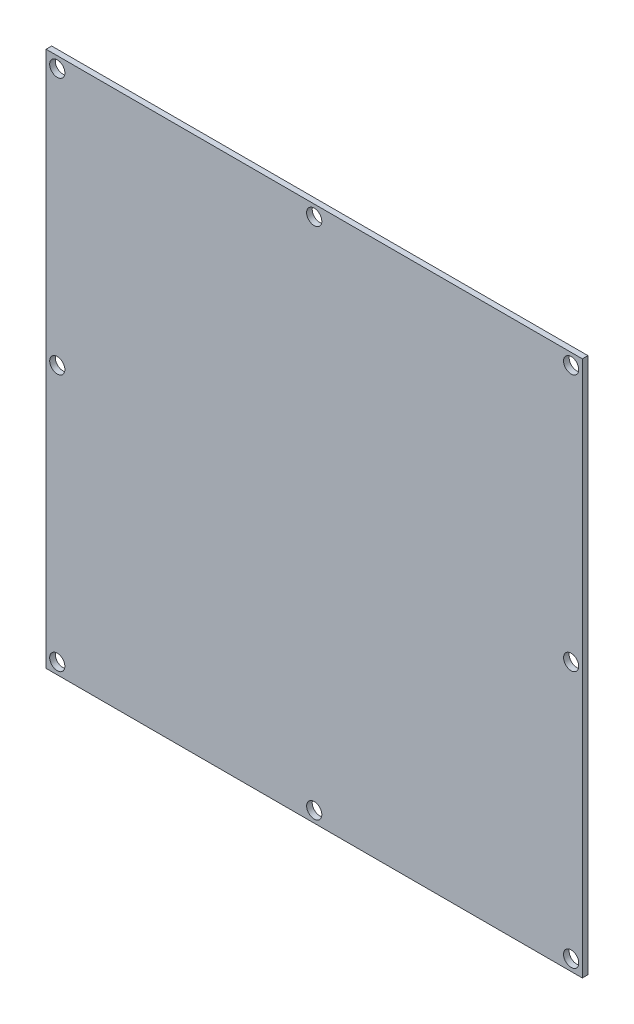
SolidWorks part; units mm, degrees
ref_plane "Front Plane" through (0, 0, 0) normal (0, 0, 1) x (1, 0, 0)
ref_plane "Top Plane" through (0, 0, 0) normal (0, 1, 0) x (1, 0, 0)
ref_plane "Right Plane" through (0, 0, 0) normal (1, 0, 0) x (0, 0, -1)
sketch "Sketch1" plane through (0, 0, 0) normal (0, 0, 1) x (1, 0, 0)
  line L1 (0, 0) -> (152.4, 0)
  line L2 (0, 0) -> (0, 152.4)
  line L3 (0, 152.4) -> (152.4, 152.4)
  line L4 (152.4, 0) -> (152.4, 152.4)
  dimension "D1" = 152.4
  dimension "D2" = 152.4
extrude "Boss-Extrude1" add sketch "Sketch1" along normal blind 1.5875
sketch "Sketch2" plane through (0, 0, 1.5875) normal (0, 0, 1) x (1, 0, 0)
  line L24 (3.175, 3.175) -> (149.225, 3.175)
  line L25 (149.225, 3.175) -> (149.225, 149.225)
  line L26 (3.175, 149.225) -> (3.175, 3.175)
  line L27 (149.225, 149.225) -> (3.175, 149.225)
  line L28 (3.175, 3.175) -> (149.225, 3.175) construction
  line L29 (149.225, 3.175) -> (149.225, 149.225) construction
  line L30 (3.175, 149.225) -> (3.175, 3.175) construction
  line L31 (149.225, 149.225) -> (3.175, 149.225) construction
  circle A0 centre (3.175, 149.225) radius 2.159
  circle A1 centre (76.2, 149.225) radius 2.159
  circle A2 centre (149.225, 149.225) radius 2.159
  circle A3 centre (3.175, 3.175) radius 2.159
  circle A4 centre (149.225, 3.175) radius 2.159
  circle A5 centre (149.225, 76.2) radius 2.159
  circle A6 centre (3.175, 76.2) radius 2.159
  circle A9 centre (76.2, 3.175) radius 2.159
  dimension "D2" = 4.318
  dimension "D1" = 3.175
extrude "Cut-Extrude1" cut sketch "Sketch2" against normal through all
